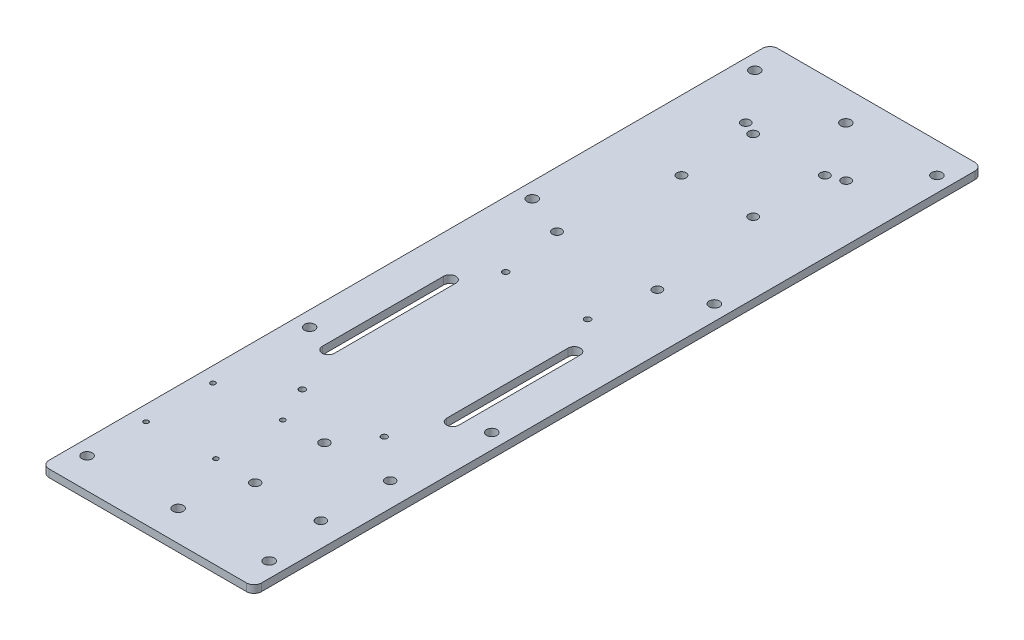
SolidWorks part; units mm, degrees
ref_plane "Front Plane" through (0, 0, 0) normal (0, 0, 1) x (1, 0, 0)
ref_plane "Top Plane" through (0, 0, 0) normal (0, 1, 0) x (1, 0, 0)
ref_plane "Right Plane" through (0, 0, 0) normal (1, 0, 0) x (0, 0, -1)
sketch "Sketch2" plane through (0, 0, 0) normal (0, 1, 0) x (1, 0, 0)
  line L0 (-44.45, 0) -> (44.45, 0) construction
  line L1 (-41.275, 152.4) -> (41.275, 152.4)
  line L2 (-44.45, 149.225) -> (-44.45, -149.225)
  line L3 (-41.275, -152.4) -> (41.275, -152.4)
  line L4 (44.45, 149.225) -> (44.45, -149.225)
  line L5 (0, 152.4) -> (0, -152.4) construction
  arc A0 (-44.45, -149.225) -> (-41.275, -152.4) centre (-41.275, -149.225) ccw
  arc A1 (41.275, -152.4) -> (44.45, -149.225) centre (41.275, -149.225) ccw
  arc A2 (41.275, 152.4) -> (44.45, 149.225) centre (41.275, 149.225) cw
  arc A3 (-41.275, 152.4) -> (-44.45, 149.225) centre (-41.275, 149.225) ccw
  point P8 (0, 0)
  point P13 (-44.45, -152.4)
  point P16 (44.45, -152.4)
  point P21 (-44.45, 152.4)
  dimension "D3" = 3.175
  dimension "D1" = 304.8
  dimension "D2" = 88.9
extrude "Plate Thickness" add sketch "Sketch2" along normal blind 3.175 contours L2 A0 L3 A1 L4 A2 L1 A3
sketch "Sketch3" plane through (0, 3.175, 0) normal (0, 1, 0) x (1, 0, 0)
  line L0 (-44.45, 149.225) -> (-44.45, -149.225) construction
  line L1 (-41.275, 152.4) -> (41.275, 152.4) construction
  line L4 (0, 152.4) -> (0, -152.4) construction
  line L5 (-41.275, -152.4) -> (41.275, -152.4) construction
  line L6 (-41.275, -152.4) -> (41.275, -152.4) construction
  circle A0 centre (-38.1, 139.7) radius 2.159
  circle A1 centre (-38.1, 46.5667) radius 2.159
  circle A2 centre (-38.1, -46.5667) radius 2.159
  circle A3 centre (-38.1, -139.7) radius 2.159
  circle A4 centre (38.1, -139.7) radius 2.159
  circle A5 centre (38.1, -46.5667) radius 2.159
  circle A6 centre (38.1, 46.5667) radius 2.159
  circle A7 centre (38.1, 139.7) radius 2.159
  circle A8 centre (0, 139.7) radius 2.159
  circle A9 centre (0, -139.7) radius 2.159
  dimension "D1" = 4.318
  dimension "D4" = 4.318
  dimension "D2" = 6.35
  dimension "D3" = 12.7
  dimension "D5" = 12.7
  dimension "D6" = 12.7
  dimension "D7" = 93.1333
  dimension "D8" = 93.1333
extrude "Mounting holes" cut sketch "Sketch3" against normal through all
sketch "Sketch4" plane through (0, 3.175, 0) normal (0, 1, 0) x (1, 0, 0)
  line L0 (-21.0058, 39.8143) -> (21.0058, 39.8143) construction
  line L1 (0, 0) -> (0, 139.7) construction
  circle A0 centre (-21.0058, 118.8083) radius 1.905
  circle A1 centre (-21.0058, 39.8143) radius 1.905
  circle A2 centre (21.0058, 39.8143) radius 1.905
  circle A3 centre (21.0058, 118.8083) radius 1.905
  point P13 (0, 39.8143)
  point P17 (0, 69.85)
  point P18 (0, 69.85)
  dimension "D1" = 3.81
  dimension "D2" = 78.994
  dimension "D3" = 42.0116
extrude "Jetson Holes (w/o mount)" cut sketch "Sketch4" against normal through all
sketch "Sketch5" plane through (0, 3.175, 0) normal (0, 1, 0) x (1, 0, 0)
  line L0 (-41.275, 152.4) -> (41.275, 152.4) construction
  line L1 (44.45, 149.225) -> (44.45, -149.225) construction
  circle A1 centre (-15.3784, 116.2839) radius 1.905
  circle A3 centre (14.619, 116.2839) radius 1.905
  circle A4 centre (14.619, 86.2865) radius 1.905
  circle A5 centre (-15.3784, 86.2865) radius 1.905
  dimension "D1" = 3.81
  dimension "D2" = 29.9974
  dimension "D4" = 36.1161
  dimension "D5" = 29.831
  dimension "D3" = 29.9974
extrude "PDB holes" cut sketch "Sketch5" against normal through all
sketch "Sketch6" plane through (0, 3.175, 0) normal (0, 1, 0) x (1, 0, 0)
  circle A6 centre (37.9835, -101.7966) radius 1.905
  circle A7 centre (17.9175, -81.7306) radius 1.905
  circle A8 centre (17.9175, -121.8626) radius 1.905
  dimension "D5" = 3.81
  dimension "D6" = 40.132
  dimension "D7" = 20.066
  dimension "D8" = 20.066
extrude "Lidar Holes" [suppressed] cut sketch "Sketch6" against normal through all
sketch "Sketch7" plane through (0, 3.175, 0) normal (0, 1, 0) x (1, 0, 0)
  line L0 (0, 152.4) -> (0, -152.4) construction
  line L1 (-41.275, 152.4) -> (41.275, 152.4) construction
  line L2 (-41.275, -152.4) -> (41.275, -152.4) construction
  line L3 (17.145, 14.4893) -> (-17.145, 14.4893) construction
  circle A0 centre (-17.145, 14.4893) radius 1.27
  circle A1 centre (-17.145, -70.6007) radius 1.27
  circle A2 centre (17.145, -70.6007) radius 1.27
  circle A3 centre (17.145, 14.4893) radius 1.27
  point P14 (0, 14.4893)
  dimension "D1" = 2.54
  dimension "D2" = 85.09
  dimension "D3" = 34.29
extrude "PixHawk Holes" cut sketch "Sketch7" against normal through all
sketch "Sketch8" plane through (0, 3.175, 0) normal (0, 1, 0) x (1, 0, 0)
  line L0 (0, 152.4) -> (0, -115.5095) construction
  line L1 (-41.275, 152.4) -> (41.275, 152.4) construction
  line L2 (-26.035, -0.006) -> (-26.035, -50.806) construction
  line L3 (-23.495, -0.006) -> (-23.495, -50.806)
  line L4 (-28.575, -0.006) -> (-28.575, -50.806)
  line L5 (26.035, -0.006) -> (26.035, -50.806) construction
  line L6 (23.495, -0.006) -> (23.495, -50.806)
  line L7 (28.575, -0.006) -> (28.575, -50.806)
  arc A0 (-23.495, -0.006) -> (-28.575, -0.006) centre (-26.035, -0.006) ccw
  arc A1 (-28.575, -50.806) -> (-23.495, -50.806) centre (-26.035, -50.806) ccw
  arc A2 (23.495, -0.006) -> (28.575, -0.006) centre (26.035, -0.006) cw
  arc A3 (28.575, -50.806) -> (23.495, -50.806) centre (26.035, -50.806) cw
  point P7 (-26.035, -25.406)
  point P14 (26.035, -25.406)
  dimension "D1" = 50.8
  dimension "D2" = 5.08
  dimension "D3" = 26.035
extrude "Battery Holes" cut sketch "Sketch8" against normal through all
sketch "Sketch9" plane through (0, 3.175, 0) normal (0, 1, 0) x (1, 0, 0)
  line L0 (44.45, 149.225) -> (44.45, -149.225) construction
  line L1 (-41.275, -152.4) -> (41.275, -152.4) construction
  circle A0 centre (6.8334, -85.3) radius 2
  circle A1 centre (34.3334, -85.3) radius 2
  circle A2 centre (34.3334, -114.3) radius 2
  circle A3 centre (6.8334, -114.3) radius 2
  dimension "D1" = 4
  dimension "D3" = 10.1166
  dimension "D5" = 38.1
  dimension "D2" = 27.5
  dimension "D4" = 29
extrude "Cut-Extrude1" cut sketch "Sketch9" against normal through all
sketch "Sketch10" plane through (0, 3.175, 0) normal (0, 1, 0) x (1, 0, 0)
  line L0 (-44.45, 149.225) -> (-44.45, -149.225) construction
  circle A0 centre (-38.1255, -87.0086) radius 1
  circle A1 centre (-38.1, -115.0086) radius 1
  circle A2 centre (-10.1266, -85.7891) radius 1
  circle A3 centre (-10.1266, -113.7891) radius 1
  point P4 (-31.7446, -101.5893)
  point P7 (-23.1772, -93.2362)
  point P10 (-23.1772, -101.5893)
  point P11 (0, 0)
  point P12 (-3.7446, -73.5893)
  point P13 (-25.3649, -101.6547)
  point P14 (0, 0)
  point P15 (0, 0)
  dimension "D1" = 2
  dimension "D2" = 28
  dimension "D3" = 28
  dimension "D4" = 28
  dimension "D5" = 6.35
extrude "Ventral Camera holes" cut sketch "Sketch10" against normal up to next
